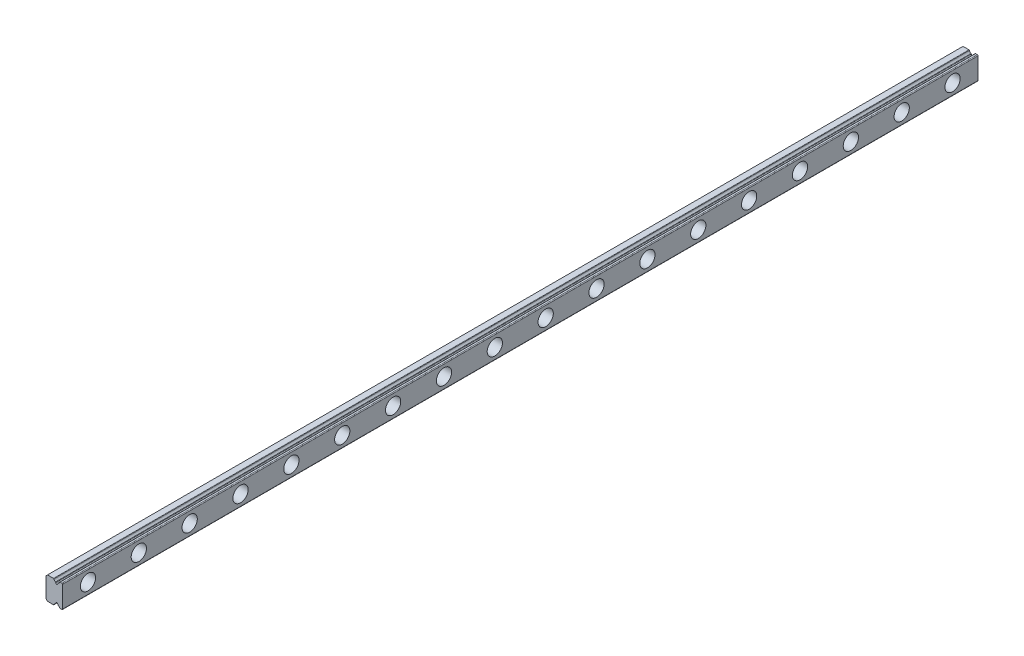
SolidWorks part; units mm, degrees
material "AISI 304"
ref_plane "前视基准面" through (0, 0, 0) normal (0, 0, 1) x (1, 0, 0)
ref_plane "上视基准面" through (0, 0, 0) normal (0, 1, 0) x (1, 0, 0)
ref_plane "右视基准面" through (0, 0, 0) normal (1, 0, 0) x (0, 0, -1)
sketch "草图1" plane through (0, 0, 0) normal (0, 0, 1) x (1, 0, 0)
  line L0 (0, 8.4) -> (0.6, 9)
  line L1 (0.6, 0) -> (2.9423, 0)
  line L2 (0, 0.6) -> (0, 8.4)
  line L3 (0.6, 9) -> (2.9423, 9)
  line L4 (6.5, 0.3) -> (6.5, 8.7)
  line L5 (0, 0.6) -> (0.6, 0)
  line L6 (4.25, 9) -> (4.25, 8) construction
  line L7 (4.25, 9) -> (4.25, 9.3) construction
  line L8 (3.85, 8) -> (3.85, 8.0351)
  line L9 (4.65, 8) -> (4.65, 8.0351)
  line L10 (5.5577, 9) -> (6.2, 9)
  line L11 (6.5, 4.5) -> (0, 4.5) construction
  line L12 (3.85, 8) -> (3.85, 8.0351)
  line L13 (4.65, 8) -> (4.65, 8.0351)
  line L14 (4.25, 0) -> (4.25, -0.3) construction
  line L15 (4.25, 0) -> (4.25, 1) construction
  line L16 (4.65, 1) -> (4.65, 0.9649)
  line L17 (3.85, 1) -> (3.85, 0.9649)
  line L18 (4.65, 1) -> (4.65, 0.9649)
  line L19 (3.85, 1) -> (3.85, 0.9649)
  line L20 (5.5577, 0) -> (6.2, 0)
  arc A0 (3.85, 8) -> (4.65, 8) centre (4.25, 8) ccw
  arc A1 (3.1291, 8.8714) -> (3.7357, 8.2158) centre (4.25, 9.3) ccw
  arc A2 (4.7643, 8.2158) -> (5.3709, 8.8714) centre (4.25, 9.3) ccw
  arc A3 (5.3709, 8.8714) -> (5.5577, 9) centre (5.5577, 8.8) cw
  arc A4 (4.65, 8.0351) -> (4.7643, 8.2158) centre (4.85, 8.0351) cw
  arc A5 (3.85, 8.0351) -> (3.7357, 8.2158) centre (3.65, 8.0351) ccw
  arc A6 (3.1291, 8.8714) -> (2.9423, 9) centre (2.9423, 8.8) ccw
  arc A7 (3.1291, 8.8714) -> (2.9423, 9) centre (2.9423, 8.8) ccw
  arc A8 (5.3709, 8.8714) -> (5.5577, 9) centre (5.5577, 8.8) cw
  arc A9 (4.65, 8.0351) -> (4.7643, 8.2158) centre (4.85, 8.0351) cw
  arc A10 (3.85, 8.0351) -> (3.7357, 8.2158) centre (3.65, 8.0351) ccw
  arc A11 (3.7357, 8.2158) -> (3.1291, 8.8714) centre (4.25, 9.3) cw
  arc A12 (5.3709, 8.8714) -> (4.7643, 8.2158) centre (4.25, 9.3) cw
  arc A13 (5.3709, 0.1286) -> (5.5577, 0) centre (5.5577, 0.2) ccw
  arc A14 (3.1291, 0.1286) -> (2.9423, 0) centre (2.9423, 0.2) cw
  arc A15 (5.3709, 0.1286) -> (4.7643, 0.7842) centre (4.25, -0.3) ccw
  arc A16 (3.7357, 0.7842) -> (3.1291, 0.1286) centre (4.25, -0.3) ccw
  arc A17 (3.85, 0.9649) -> (3.7357, 0.7842) centre (3.65, 0.9649) cw
  arc A18 (4.65, 0.9649) -> (4.7643, 0.7842) centre (4.85, 0.9649) ccw
  arc A19 (3.85, 0.9649) -> (3.7357, 0.7842) centre (3.65, 0.9649) cw
  arc A20 (4.65, 0.9649) -> (4.7643, 0.7842) centre (4.85, 0.9649) ccw
  arc A21 (4.7643, 0.7842) -> (5.3709, 0.1286) centre (4.25, -0.3) cw
  arc A22 (3.1291, 0.1286) -> (3.7357, 0.7842) centre (4.25, -0.3) cw
  arc A23 (3.85, 1) -> (4.65, 1) centre (4.25, 1) cw
  arc A24 (6.2, 0) -> (6.5, 0.3) centre (6.2, 0.3) ccw
  arc A25 (6.2, 9) -> (6.5, 8.7) centre (6.2, 8.7) cw
  point P0 (0, 0)
  point P2 (0, 9)
  point P24 (5.4119, 9)
  point P27 (4.65, 8.1686)
  point P49 (4.65, 0.8314)
  point P50 (5.4119, 0)
  point P53 (6.5, 0)
  dimension "D3" = 1
  dimension "D7" = 0.8
  dimension "D9" = 2.4
  dimension "D10" = 0.2
  dimension "D11" = 0.3
  dimension "D1" = 6.5
  dimension "D2" = 9
  dimension "D4" = 2.25
  dimension "D8" = 0.3
extrude "凸台-拉伸1" add sketch "草图1" along normal blind 360 contours A25 L10 A3 A2 A4 L9 A0 L8 A5 A1 A6 L3 L0 L2 L5 L1 A14 A16 A17 L17 A23 L16 A18 A15 A13 L20 A24 L4
sketch "草图2" plane through (6.5, 0, 0) normal (1, 0, 0) x (0, 0, -1)
  line L0 (-360, 4.5) -> (-350, 4.5) construction
  line L1 (-360, 0.3) -> (-360, 8.7) construction
  line L2 (-350, 4.5) -> (-10, 4.5) construction
  line L3 (-10, 4.5) -> (0, 4.5) construction
  line L4 (0, 0.3) -> (0, 8.7) construction
  line L5 (-10, 4.5) -> (-30, 4.5) construction
  circle A0 centre (-10, 4.5) radius 3
  circle A1 centre (-30, 4.5) radius 3
  circle A2 centre (-50, 4.5) radius 3
  circle A3 centre (-70, 4.5) radius 3
  circle A4 centre (-90, 4.5) radius 3
  circle A5 centre (-110, 4.5) radius 3
  circle A6 centre (-130, 4.5) radius 3
  circle A7 centre (-150, 4.5) radius 3
  circle A8 centre (-170, 4.5) radius 3
  circle A9 centre (-190, 4.5) radius 3
  circle A10 centre (-210, 4.5) radius 3
  circle A11 centre (-230, 4.5) radius 3
  circle A12 centre (-250, 4.5) radius 3
  circle A13 centre (-270, 4.5) radius 3
  circle A14 centre (-290, 4.5) radius 3
  circle A15 centre (-310, 4.5) radius 3
  circle A16 centre (-330, 4.5) radius 3
  circle A17 centre (-350, 4.5) radius 3
  circle A18 centre (-370, 4.5) radius 3
  circle A19 centre (-390, 4.5) radius 3
  circle A20 centre (-410, 4.5) radius 3
  circle A21 centre (-430, 4.5) radius 3
  circle A22 centre (-450, 4.5) radius 3
  circle A23 centre (-470, 4.5) radius 3
  circle A24 centre (-490, 4.5) radius 3
  circle A25 centre (-510, 4.5) radius 3
  circle A26 centre (-530, 4.5) radius 3
  circle A27 centre (-550, 4.5) radius 3
  circle A28 centre (-570, 4.5) radius 3
  circle A29 centre (-590, 4.5) radius 3
  circle A30 centre (-610, 4.5) radius 3
  circle A31 centre (-630, 4.5) radius 3
  circle A32 centre (-650, 4.5) radius 3
  circle A33 centre (-670, 4.5) radius 3
  circle A34 centre (-690, 4.5) radius 3
  circle A35 centre (-710, 4.5) radius 3
  circle A36 centre (-730, 4.5) radius 3
  circle A37 centre (-750, 4.5) radius 3
  circle A38 centre (-770, 4.5) radius 3
  circle A39 centre (-790, 4.5) radius 3
  circle A40 centre (-810, 4.5) radius 3
  circle A41 centre (-830, 4.5) radius 3
  circle A42 centre (-850, 4.5) radius 3
  circle A43 centre (-870, 4.5) radius 3
  circle A44 centre (-890, 4.5) radius 3
  circle A45 centre (-910, 4.5) radius 3
  circle A46 centre (-930, 4.5) radius 3
  circle A47 centre (-950, 4.5) radius 3
  circle A48 centre (-970, 4.5) radius 3
  circle A49 centre (-990, 4.5) radius 3
  circle A50 centre (-1010, 4.5) radius 3
  circle A51 centre (-1030, 4.5) radius 3
  circle A52 centre (-1050, 4.5) radius 3
  circle A53 centre (-1070, 4.5) radius 3
  circle A54 centre (-1090, 4.5) radius 3
  circle A55 centre (-1110, 4.5) radius 3
  circle A56 centre (-1130, 4.5) radius 3
  circle A57 centre (-1150, 4.5) radius 3
  circle A58 centre (-1170, 4.5) radius 3
  circle A59 centre (-1190, 4.5) radius 3
  circle A60 centre (-1210, 4.5) radius 3
  circle A61 centre (-1230, 4.5) radius 3
  circle A62 centre (-1250, 4.5) radius 3
  circle A63 centre (-1270, 4.5) radius 3
  circle A64 centre (-1290, 4.5) radius 3
  circle A65 centre (-1310, 4.5) radius 3
  circle A66 centre (-1330, 4.5) radius 3
  circle A67 centre (-1350, 4.5) radius 3
  circle A68 centre (-1370, 4.5) radius 3
  circle A69 centre (-1390, 4.5) radius 3
  circle A70 centre (-1410, 4.5) radius 3
  circle A71 centre (-1430, 4.5) radius 3
  circle A72 centre (-1450, 4.5) radius 3
  circle A73 centre (-1470, 4.5) radius 3
  circle A74 centre (-1490, 4.5) radius 3
  circle A75 centre (-1510, 4.5) radius 3
  circle A76 centre (-1530, 4.5) radius 3
  circle A77 centre (-1550, 4.5) radius 3
  circle A78 centre (-1570, 4.5) radius 3
  circle A79 centre (-1590, 4.5) radius 3
  circle A80 centre (-1610, 4.5) radius 3
  circle A81 centre (-1630, 4.5) radius 3
  circle A82 centre (-1650, 4.5) radius 3
  circle A83 centre (-1670, 4.5) radius 3
  circle A84 centre (-1690, 4.5) radius 3
  circle A85 centre (-1710, 4.5) radius 3
  circle A86 centre (-1730, 4.5) radius 3
  circle A87 centre (-1750, 4.5) radius 3
  circle A88 centre (-1770, 4.5) radius 3
  circle A89 centre (-1790, 4.5) radius 3
  circle A90 centre (-1810, 4.5) radius 3
  circle A91 centre (-1830, 4.5) radius 3
  circle A92 centre (-1850, 4.5) radius 3
  circle A93 centre (-1870, 4.5) radius 3
  circle A94 centre (-1890, 4.5) radius 3
  circle A95 centre (-1910, 4.5) radius 3
  circle A96 centre (-1930, 4.5) radius 3
  circle A97 centre (-1950, 4.5) radius 3
  circle A98 centre (-1970, 4.5) radius 3
  circle A99 centre (-1990, 4.5) radius 3
  circle A100 centre (-2010, 4.5) radius 3
  circle A101 centre (-2030, 4.5) radius 3
  circle A102 centre (-2050, 4.5) radius 3
  circle A103 centre (-2070, 4.5) radius 3
  circle A104 centre (-2090, 4.5) radius 3
  circle A105 centre (-2110, 4.5) radius 3
  circle A106 centre (-2130, 4.5) radius 3
  circle A107 centre (-2150, 4.5) radius 3
  circle A108 centre (-2170, 4.5) radius 3
  circle A109 centre (-2190, 4.5) radius 3
  circle A110 centre (-2210, 4.5) radius 3
  circle A111 centre (-2230, 4.5) radius 3
  circle A112 centre (-2250, 4.5) radius 3
  circle A113 centre (-2270, 4.5) radius 3
  circle A114 centre (-2290, 4.5) radius 3
  circle A115 centre (-2310, 4.5) radius 3
  circle A116 centre (-2330, 4.5) radius 3
  circle A117 centre (-2350, 4.5) radius 3
  circle A118 centre (-2370, 4.5) radius 3
  circle A119 centre (-2390, 4.5) radius 3
  circle A120 centre (-2410, 4.5) radius 3
  circle A121 centre (-2430, 4.5) radius 3
  circle A122 centre (-2450, 4.5) radius 3
  circle A123 centre (-2470, 4.5) radius 3
  dimension "D2" = 6
  dimension "D1" = 10
  dimension "D4" = 20
  dimension "D3" = 25
  dimension "D5" = 100
extrude "切除-拉伸1" cut sketch "草图2" against normal blind 4.5
sketch "草图3" plane through (2, 0, 0) normal (1, 0, 0) x (0, 0, -1)
  line L0 (-10, 4.5) -> (-30, 4.5) construction
  circle A0 centre (-10, 4.5) radius 1.75
  circle A1 centre (-30, 4.5) radius 1.75
  circle A2 centre (-50, 4.5) radius 1.75
  circle A3 centre (-70, 4.5) radius 1.75
  circle A4 centre (-90, 4.5) radius 1.75
  circle A5 centre (-110, 4.5) radius 1.75
  circle A6 centre (-130, 4.5) radius 1.75
  circle A7 centre (-150, 4.5) radius 1.75
  circle A8 centre (-170, 4.5) radius 1.75
  circle A9 centre (-190, 4.5) radius 1.75
  circle A10 centre (-210, 4.5) radius 1.75
  circle A11 centre (-230, 4.5) radius 1.75
  circle A12 centre (-250, 4.5) radius 1.75
  circle A13 centre (-270, 4.5) radius 1.75
  circle A14 centre (-290, 4.5) radius 1.75
  circle A15 centre (-310, 4.5) radius 1.75
  circle A16 centre (-330, 4.5) radius 1.75
  circle A17 centre (-350, 4.5) radius 1.75
  circle A18 centre (-370, 4.5) radius 1.75
  circle A19 centre (-390, 4.5) radius 1.75
  circle A20 centre (-410, 4.5) radius 1.75
  circle A21 centre (-430, 4.5) radius 1.75
  circle A22 centre (-450, 4.5) radius 1.75
  circle A23 centre (-470, 4.5) radius 1.75
  circle A24 centre (-490, 4.5) radius 1.75
  circle A25 centre (-510, 4.5) radius 1.75
  circle A26 centre (-530, 4.5) radius 1.75
  circle A27 centre (-550, 4.5) radius 1.75
  circle A28 centre (-570, 4.5) radius 1.75
  circle A29 centre (-590, 4.5) radius 1.75
  circle A30 centre (-610, 4.5) radius 1.75
  circle A31 centre (-630, 4.5) radius 1.75
  circle A32 centre (-650, 4.5) radius 1.75
  circle A33 centre (-670, 4.5) radius 1.75
  circle A34 centre (-690, 4.5) radius 1.75
  circle A35 centre (-710, 4.5) radius 1.75
  circle A36 centre (-730, 4.5) radius 1.75
  circle A37 centre (-750, 4.5) radius 1.75
  circle A38 centre (-770, 4.5) radius 1.75
  circle A39 centre (-790, 4.5) radius 1.75
  circle A40 centre (-810, 4.5) radius 1.75
  circle A41 centre (-830, 4.5) radius 1.75
  circle A42 centre (-850, 4.5) radius 1.75
  circle A43 centre (-870, 4.5) radius 1.75
  circle A44 centre (-890, 4.5) radius 1.75
  circle A45 centre (-910, 4.5) radius 1.75
  circle A46 centre (-930, 4.5) radius 1.75
  circle A47 centre (-950, 4.5) radius 1.75
  circle A48 centre (-970, 4.5) radius 1.75
  circle A49 centre (-990, 4.5) radius 1.75
  circle A50 centre (-1010, 4.5) radius 1.75
  circle A51 centre (-1030, 4.5) radius 1.75
  circle A52 centre (-1050, 4.5) radius 1.75
  circle A53 centre (-1070, 4.5) radius 1.75
  dimension "D1" = 3.5
  dimension "D3" = 20
  dimension "D2" = 25
  dimension "D4" = 30
extrude "切除-拉伸2" cut sketch "草图3" against normal through all
